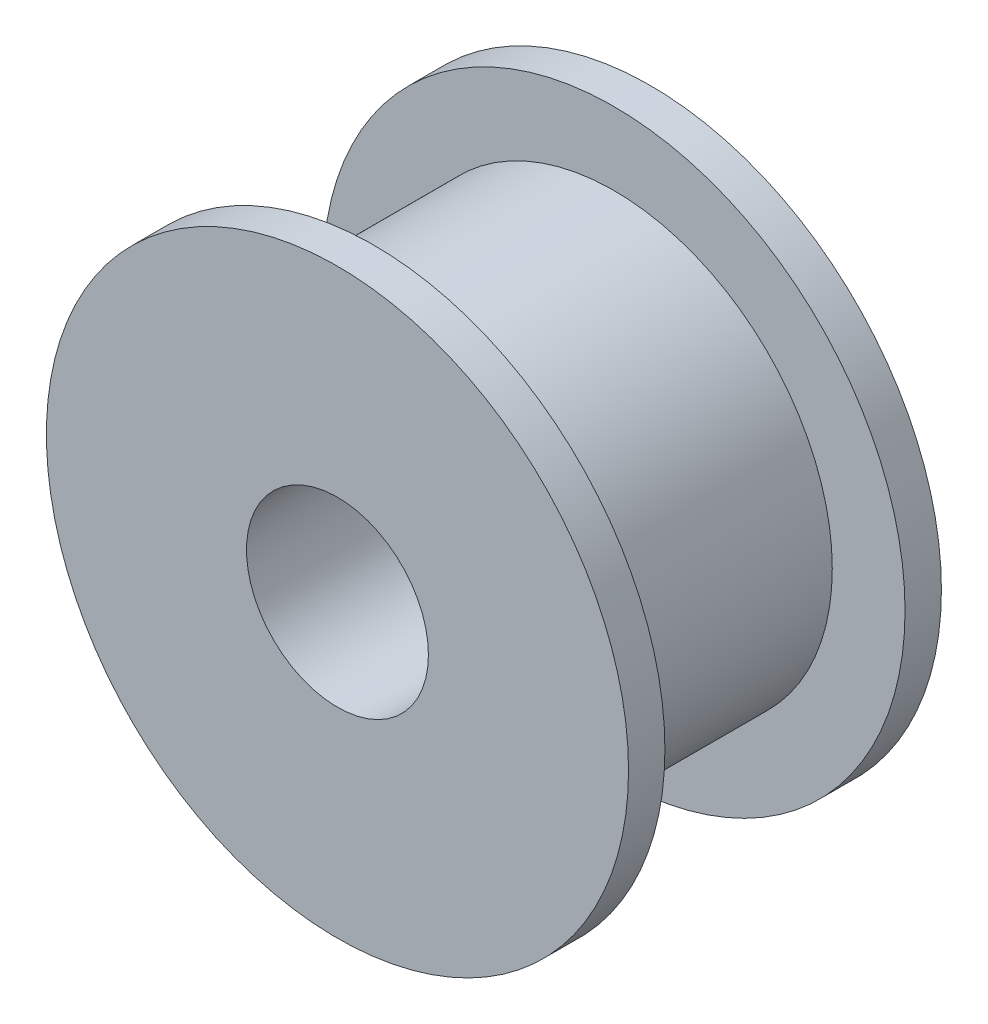
SolidWorks part; units mm, degrees
ref_plane "Alzado" through (0, 0, 0) normal (0, 0, 1) x (1, 0, 0)
ref_plane "Planta" through (0, 0, 0) normal (0, 1, 0) x (1, 0, 0)
ref_plane "Vista lateral" through (0, 0, 0) normal (1, 0, 0) x (0, 0, -1)
sketch "Croquis1" plane through (0, 0, 0) normal (0, 0, 1) x (1, 0, 0)
  circle A0 centre (0, 0) radius 8
  circle A1 centre (0, 0) radius 2.5
  dimension "D1" = 16
  dimension "D2" = 5
extrude "Saliente-Extruir1" add sketch "Croquis1" along normal blind 1
sketch "Croquis2" plane through (0, 0, 1) normal (0, 0, 1) x (1, 0, 0)
  circle A0 centre (0, 0) radius 6
  circle A1 centre (0, 0) radius 2.5
  dimension "D1" = 12
extrude "Saliente-Extruir2" add sketch "Croquis2" along normal blind 6.6
sketch "Croquis3" plane through (0, 0, 7.6) normal (0, 0, 1) x (1, 0, 0)
  circle A0 centre (0, 0) radius 8
  circle A1 centre (0, 0) radius 2.5
  dimension "D1" = 16
extrude "Saliente-Extruir3" add sketch "Croquis3" along normal blind 1
